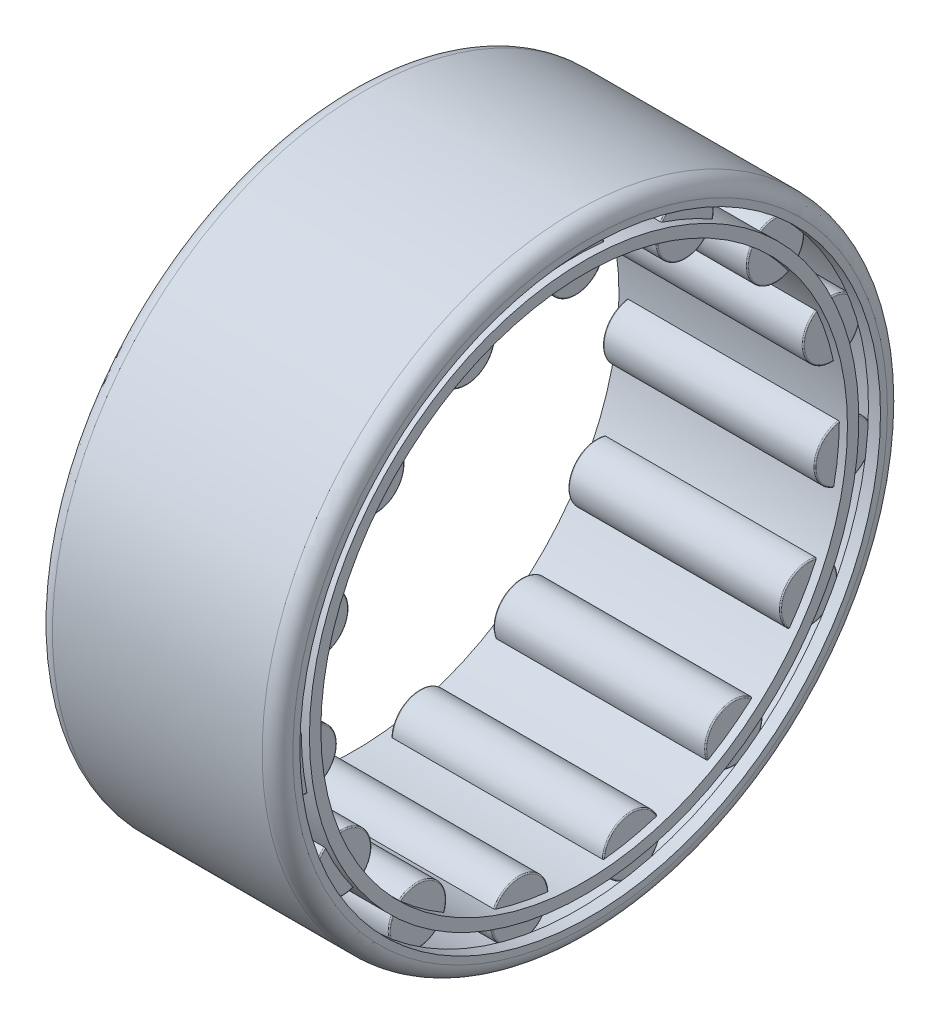
SolidWorks part; units mm, degrees
ref_plane "Plane1" through (0, 0, 0) normal (0, 0, 1) x (1, 0, 0)
ref_plane "Plane2" through (0, 0, 0) normal (0, 1, 0) x (1, 0, 0)
ref_plane "Plane3" through (0, 0, 0) normal (1, 0, 0) x (0, 0, -1)
sketch "Clipboard" plane through (0, 0, 0) normal (0, 0, 1) x (1, 0, 0)
  line L0 (-10, 0) -> (10, 0) construction
  line L1 (41.1529, 1.4371) -> (62.7517, -4.3503)
  line L2 (41.1529, 1.4371) -> (75.4583, 10.6292)
  line L3 (41.1529, 1.4371) -> (62.7517, -4.3503)
  line L4 (41.1529, 1.4371) -> (-22.3471, -0.7804)
  dimension "BallCLRad" = 35.5155
  dimension "Count" = 15
  dimension "Show_count" = 15
  dimension "Max_count" = 15
  dimension "Min_count" = 2
  dimension "Bore" = 63.5
sketch "InnRacSke" plane through (0, 0, 0) normal (0, 0, 1) x (1, 0, 0)
  line L0 (-14.2875, 38.3286) -> (-15.875, 38.3286)
  line L1 (-15.875, 38.3286) -> (-15.875, 39.243)
  line L2 (-13.843, 41.275) -> (13.843, 41.275)
  line L4 (15.875, 39.243) -> (15.875, 38.3286)
  line L5 (15.875, 38.3286) -> (14.2875, 38.3286)
  line L6 (14.2875, 38.3286) -> (14.2875, 39.2811)
  line L7 (14.2875, 39.2811) -> (-14.2875, 39.2811)
  line L8 (-14.2875, 39.2811) -> (-14.2875, 38.3286)
  line L9 (-31.75, 0) -> (31.75, 0) construction
  arc A0 (-15.875, 39.243) -> (-13.843, 41.275) centre (-13.843, 39.243) cw
  arc A2 (13.843, 41.275) -> (15.875, 39.243) centre (13.843, 39.243) cw
  dimension "radius" = 2.032
  dimension "D1" = 78.5622
  dimension "OD" = 82.55
  dimension "Width" = 31.75
  dimension "groove_dp" = 0.9525
  dimension "Cyl_Len" = 28.575
  dimension "halfCyl" = 14.2875
revolve "Race" add sketch "InnRacSke" angle 360 about L9
sketch "RolDetSke" plane through (0, 0, 0) normal (0, 0, 1) x (1, 0, 0)
  line L0 (-14.0018, 39.131) -> (-14.0017, 35.5155)
  line L1 (-14.0017, 35.5155) -> (14.0017, 35.5155)
  line L2 (14.0017, 35.5155) -> (14.0018, 39.131)
  line L3 (13.8511, 39.2816) -> (-13.8511, 39.2816)
  line L4 (-28.575, 35.5155) -> (28.575, 35.5155) construction
  arc A0 (14.0018, 39.131) -> (13.8511, 39.2816) centre (13.8511, 39.131) ccw
  arc A1 (-13.8511, 39.2816) -> (-14.0018, 39.131) centre (-13.8511, 39.131) ccw
  dimension "Roller_radius" = 0.1506
  dimension "Roller_diameter" = 7.5321
  dimension "Roller_length" = 28.0035
  dimension "RollerCLRad" = 35.5155
  dimension "halfLength" = 14.0017
revolve "RollerDetailed" add sketch "RolDetSke" angle 360 about L4
ref_axis "Axis1" through (-50, 0, 0) along (1, 0, 0)
sketch "CagSpiSke" plane through (0, 0, 0) normal (0, 0, 1) x (1, 0, 0)
  line L0 (15.0812, 34.7623) -> (15.0812, 36.2688)
  line L1 (15.0812, 36.2688) -> (-15.0813, 36.2688)
  line L2 (-15.0813, 36.2688) -> (-15.0813, 34.7623)
  line L3 (-15.0813, 34.7623) -> (15.0812, 34.7623)
  line L4 (-31.75, 0) -> (31.75, 0) construction
  dimension "Cage_width" = 30.1625
  dimension "D2" = 69.5247
  dimension "Cage_thickness" = 1.5064
  dimension "halfWidth" = 15.0813
revolve "CageSpine" add sketch "CagSpiSke" angle 360 about L4
pattern_circular "RollersDetailed" count 15 every 24 about axis through (-50, 0, 0) along (1, 0, 0) of "RollerDetailed"
sketch "RolSimSke" plane through (0, 0, 0) normal (0, 0, 1) x (1, 0, 0)
  line L0 (-25.4, 0) -> (25.4, 0) construction
  line L2 (-13.8511, 39.2821) -> (13.8511, 39.2821)
  line L3 (-14.0018, 39.1315) -> (-14.0018, 31.9006)
  line L4 (-13.8511, 31.75) -> (13.8511, 31.75)
  line L5 (14.0017, 39.1315) -> (14.0017, 31.9006)
  arc A0 (-14.0018, 31.9006) -> (-13.8511, 31.75) centre (-13.8511, 31.9006) ccw
  arc A1 (-13.8511, 39.2821) -> (-14.0018, 39.1315) centre (-13.8511, 39.1315) ccw
  arc A2 (14.0017, 39.1315) -> (13.8511, 39.2821) centre (13.8511, 39.1315) ccw
  arc A3 (13.8511, 31.75) -> (14.0017, 31.9006) centre (13.8511, 31.9006) ccw
  point P10 (-14.0018, 31.75)
  point P15 (14.0017, 39.2821)
  point P18 (14.0017, 31.75)
  dimension "Bore" = 63.5
  dimension "Roller_diameter" = 7.5321
  dimension "Roller_length" = 28.0035
  dimension "D1" = 0.1506
  dimension "halfWidth" = 14.0017
revolve "RollersSimplified" [suppressed] add sketch "RolSimSke" angle 360 about L0
equation "\"BallCLRad@Clipboard\" =  ( \"D1@InnRacSke\" + \"Bore@Clipboard\" )  / 4"
equation "\"RollerCLRad@RolDetSke\" = \"BallCLRad@Clipboard\""
equation "\"halfCyl@InnRacSke\" = \"Cyl_Len@InnRacSke\" / 2"
equation "\"Roller_diameter@RolDetSke\" =  ( \"D1@InnRacSke\" - \"Bore@Clipboard\" )  / 2 + .001"
equation "\"Roller_radius@RolDetSke\" = \"Roller_diameter@RolDetSke\" / 50"
equation "\"Roller_length@RolDetSke\" = \"Cyl_Len@InnRacSke\" * .98"
equation "\"halfLength@RolDetSke\" = \"Roller_length@RolDetSke\" / 2"
equation "\"Cage_width@CagSpiSke\" =  ( \"Cyl_Len@InnRacSke\" + \"Width@InnRacSke\" )  / 2"
equation "\"halfWidth@CagSpiSke\" = \"Cage_width@CagSpiSke\" / 2"
equation "\"Cage_thickness@CagSpiSke\"  = \"Roller_diameter@RolDetSke\" / 5"
equation "\"D2@CagSpiSke\" =  \"RollerCLRad@RolDetSke\" * 2 - \"Cage_thickness@CagSpiSke\""
equation "\"Roller_length@RolSimSke\" = \"Cyl_Len@InnRacSke\" * .98"
equation "\"halfWidth@RolSimSke\" = \"Roller_length@RolSimSke\" / 2"
equation "\"D1@RolSimSke\" = \"Roller_radius@RolDetSke\""
equation "\"Roller_diameter@RolSimSke\" =  ( \"D1@InnRacSke\" - \"Bore@Clipboard\" )  / 2 + .001"
equation "\"Max_count@Clipboard\" = int( 3.14159265 / atn(( \"Roller_diameter@RolDetSke\" / 2) / sqr( \"RollerCLRad@RolDetSke\"  *  \"RollerCLRad@RolDetSke\" - ( \"Roller_diameter@RolDetSke\" / 2) *  ( \"Roller_diameter@RolDetSke\" / 2))))"
equation "\"Max_count@Clipboard\" = ((sgn( \"Max_count@Clipboard\" - \"Count@Clipboard\" )-1)*( \"Max_count@Clipboard\" - \"Count@Clipboard\" ))/-2+ \"Count@Clipboard\""
equation "\"Count@RollersDetailed\" = int( \"Show_count@Clipboard\" ) "
equation "\"Count@RollersDetailed\" = ((sgn( \"Count@RollersDetailed\" - \"Max_count@Clipboard\" )-1)*( \"Count@RollersDetailed\" - \"Max_count@Clipboard\" ))/-2+ \"Max_count@Clipboard\""
equation "\"Count@RollersDetailed\" = ((sgn( \"Count@RollersDetailed\" - \"Min_count@Clipboard\" )+1)*( \"Count@RollersDetailed\" - \"Min_count@Clipboard\"))/2 +\"Min_count@Clipboard\""
equation "\"Angle@RollersDetailed\" = 360.0 / \"Max_count@Clipboard\""
equation "\"Angle@CageSpine\" =  \"Angle@RollersDetailed\" * ( \"Count@RollersDetailed\" -1 + int( \"Count@RollersDetailed\" / \"Max_count@Clipboard\" ) )  + 0.001 -  int( \"Count@RollersDetailed\" / \"Max_count@Clipboard\" ) * 0.001"
equation "\"Angle@CageSpine\" =  \"Angle@CageSpine\" * int( \"Min_count@Clipboard\" / 2) + int(1 / \"Min_count@Clipboard\")  * 0.001"
equation "\"Bore@RolSimSke\" = \"Bore@Clipboard\""
